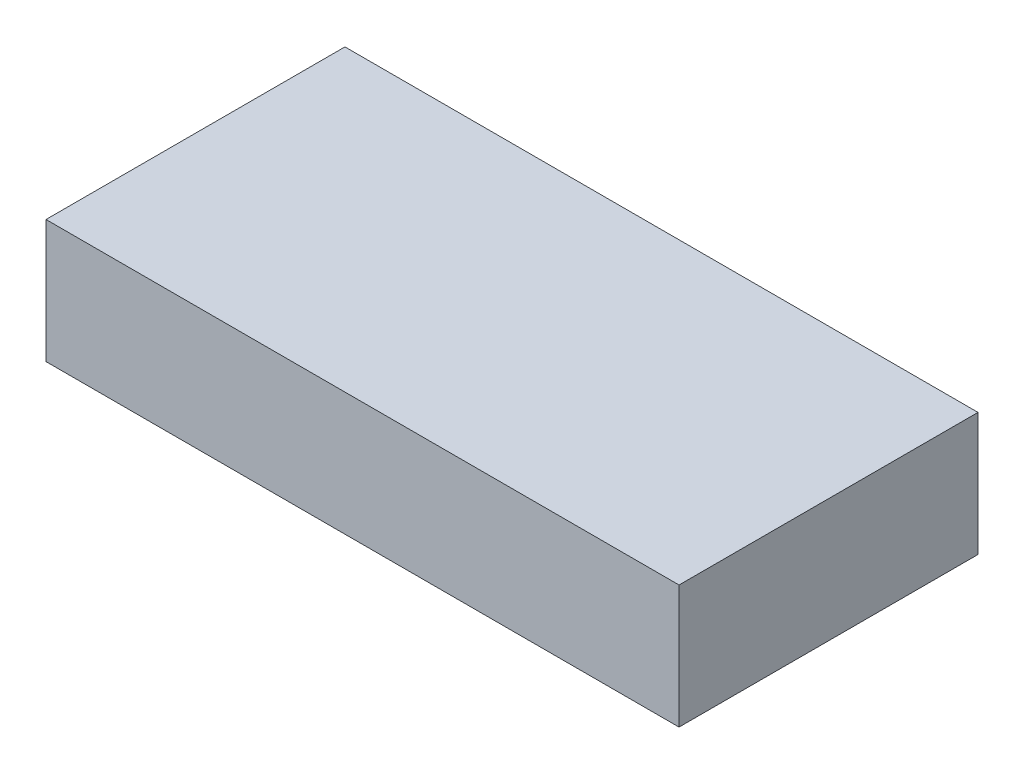
SolidWorks part; units mm, degrees
ref_plane "Front Plane" through (0, 0, 0) normal (0, 0, 1) x (1, 0, 0)
ref_plane "Top Plane" through (0, 0, 0) normal (0, 1, 0) x (1, 0, 0)
ref_plane "Right Plane" through (0, 0, 0) normal (1, 0, 0) x (0, 0, -1)
sketch "Sketch1" plane through (0, 0, 0) normal (0, 1, 0) x (1, 0, 0)
  line L1 (0, 0) -> (72, 0)
  line L2 (0, 0) -> (0, 34)
  line L3 (0, 34) -> (72, 34)
  line L4 (72, 0) -> (72, 34)
  dimension "D1" = 72
  dimension "D2" = 34
extrude "Boss-Extrude1" add sketch "Sketch1" along normal blind 14
